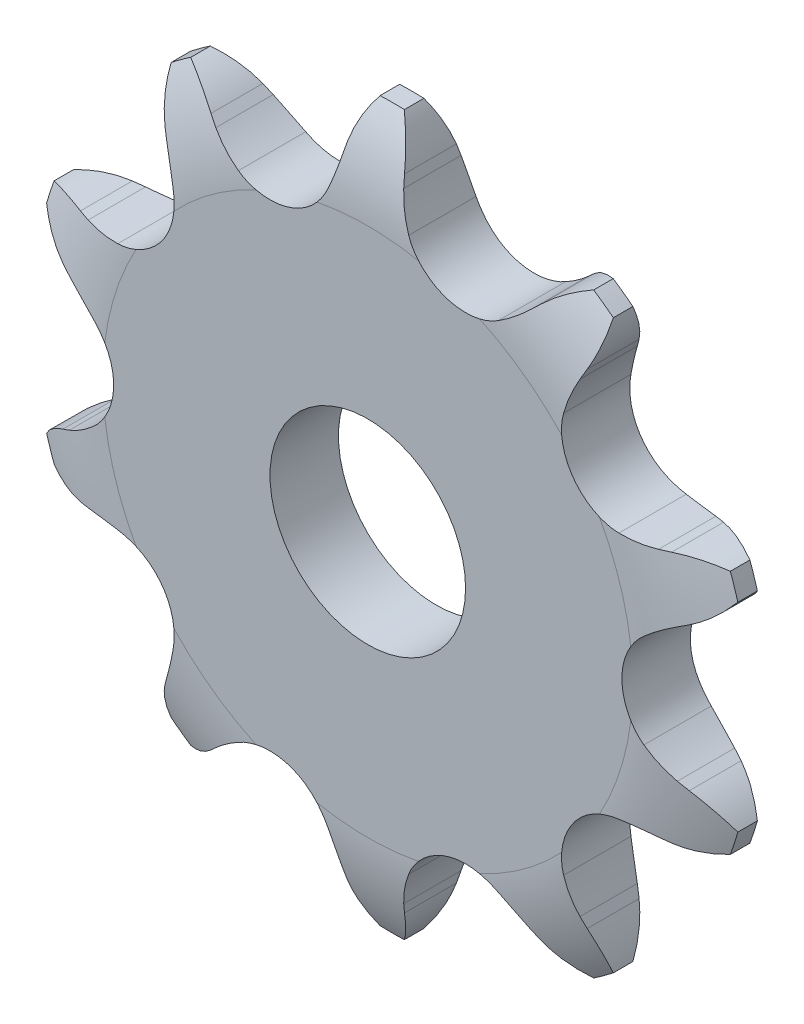
SolidWorks part; units mm, degrees
ref_plane "Front Plane" through (0, 0, 0) normal (0, 0, 1) x (1, 0, 0)
ref_plane "Top Plane" through (0, 0, 0) normal (0, 1, 0) x (1, 0, 0)
ref_plane "Right Plane" through (0, 0, 0) normal (1, 0, 0) x (0, 0, -1)
sketch "Sketch0" plane through (0, 0, 0) normal (0, 0, 1) x (1, 0, 0)
  line L0 (4, -12.3107) -> (0, 0) construction
  line L1 (0, 0) -> (10.4721, -7.6085) construction
  line L2 (0, 0) -> (-4, -12.3107) construction
  line L3 (4, -12.3107) -> (10.4721, -7.6085) construction
  line L4 (4, -12.3107) -> (-4, -12.3107) construction
  line L5 (6.7522, -11.2745) -> (6.4407, -10.9799)
  line L6 (4, -12.3107) -> (0, -13.6104) construction
  line L7 (1.1643, -13.0901) -> (1.2432, -12.6687)
  line L8 (0, -12.3107) -> (0, -14.7107) construction
  line L9 (5.3137, -10.1244) -> (1.9398, -15.7394) construction
  line L10 (0, 0) -> (0, -12.3107) construction
  line L11 (6.4407, -10.9799) -> (1.9398, -15.7394) construction
  line L12 (0, -14.7107) -> (0, -15.3022) construction
  line L13 (9.6631, -8.1962) -> (6.7522, -11.2745) construction
  circle A0 centre (0, 0) radius 14.7107 construction
  circle A1 centre (0, 0) radius 12.9443 construction
  arc A2 (-4.0031, -16.4269) -> (12.8941, -10.9367) centre (0, 0) ccw
  circle A3 centre (0, 0) radius 15.3022 construction
  circle A4 centre (4, -12.3107) radius 2.5 construction
  arc A7 (5.3137, -10.1244) -> (1.6522, -11.3141) centre (4, -12.3107) ccw
  circle A8 centre (4, -12.3107) radius 2.5506 construction
  arc A9 (6.7522, -11.2745) -> (12.8941, -10.9367) centre (9.6631, -8.1962) ccw
  arc A10 (6.4407, -10.9799) -> (5.3137, -10.1244) centre (1.9398, -15.7394) ccw
  arc A11 (1.1643, -13.0901) -> (-4.0031, -16.4269) centre (-3, -12.3107) cw
  arc A12 (1.2432, -12.6687) -> (1.6522, -11.3141) centre (7.682, -13.8737) cw
  dimension "D1" = 2.5506
  dimension "R" = 2.5506
sketch "Sketch1" plane through (0, 0, 0) normal (1, 0, 0) x (0, 0, -1)
  line L0 (1.4, 0) -> (-1.4, 0)
  line L1 (-1.4, 0) -> (-1.4, 10.8378)
  line L2 (-1.4, 12.9443) -> (0, 12.9443) construction
  line L3 (-0.4, 14.7107) -> (0.4, 14.7107)
  line L5 (1.4, 10.8378) -> (1.4, 0)
  line L7 (0, 14.7107) -> (0, 0) construction
  line L8 (-1.4, 10.8378) -> (1.4, 10.8378) construction
  line L9 (0, 14.7107) -> (0, -14.7107) construction
  line L10 (-1.4, 10.8378) -> (-1.4, 14.7107) construction
  line L11 (-1.4, 14.7107) -> (-0.4, 14.7107) construction
  line L12 (0.4, 14.7107) -> (1.4, 14.7107) construction
  line L13 (1.4, 14.7107) -> (1.4, 10.8378) construction
  line L14 (0, 0) -> (-6.4008, 0) construction
  line L15 (-1.4, 12.9443) -> (-1.4, 7.6443) construction
  line L22 (1.4, 0) -> (-10.6, 0) construction
  line L24 (-1.4, 0) -> (-1.4, 7.6443) construction
  arc A0 (-0.4, 14.7107) -> (-1.4, 10.8378) centre (6.6, 10.8378) ccw
  arc A1 (0.4, 14.7107) -> (1.4, 10.8378) centre (-6.6, 10.8378) cw
  dimension "R" = 8
revolve "Revolve1" add sketch "Sketch1" angle 360 mid plane about L0
extrude "Cut-Extrude1" cut sketch "Sketch0" against normal through all and the other way through all
pattern_circular "CirPattern1" count 10 over 360 about axis through (0, 0, 0) along (0, 0, 1) of "Cut-Extrude1"
sketch "Sketch2" plane through (0, 0, 0) normal (0, 0, 1) x (1, 0, 0)
  circle A0 centre (0, 0) radius 4 construction
  circle A1 centre (0, 0) radius 8.5
  circle A2 centre (0, 0) radius 14.71 construction
  dimension "Bore" = 8
  dimension "Hub Dia." = 17
  dimension "OD" = 29.42
extrude "Boss-Extrude1" add sketch "Sketch2" along normal up to vertex (10.6 mm away) from surface at 1.4 starting at face at (0, 0, 1.4)
sketch "Sketch3" plane through (0, 0, 0) normal (0, 0, 1) x (1, 0, 0)
  circle A0 centre (0, 0) radius 4 construction
  circle A1 centre (0, 0) radius 4
extrude "Cut-Extrude2" cut sketch "Sketch3" along normal through all and the other way through all
sketch "Sketch4" plane through (0, 0, 0) normal (1, 0, 0) x (0, 0, -1)
  line L0 (-10.6, 8.5) -> (-10.6, 8)
  line L1 (-1.4, 14.7107) -> (-3.5, 14.7107)
  line L2 (-1.4, 14.7107) -> (-1.4, 7.6443)
  line L3 (-1.4, 7.6443) -> (-3.5, 7.6443)
  line L4 (-3.5, 14.7107) -> (-3.5, 7.6443)
  line L9 (-10.6, 8) -> (-10.1, 8.5)
  line L10 (-10.1, 8.5) -> (-10.6, 8.5)
  dimension "C" = 0.5
  dimension "D3" = 2.1
revolve "Cut-Revolve1" cut sketch "Sketch4" angle 360 mid plane about L22
sketch "Sketch5" plane through (0, 0, 0) normal (0, 0, 1) x (1, 0, 0)
  circle A0 centre (0, 0) radius 14.71 construction
  circle A1 centre (0, 0) radius 14.71
extrude "Cut-Extrude3" [suppressed] cut sketch "Sketch5" against normal through all and the other way through all flip side to cut
sketch "Sketch6" plane through (0, 0, 1.4) normal (0, 0, 1) x (1, 0, 0)
  circle A0 centre (0, 0) radius 9
  dimension "D1" = 18
extrude "Cut-Extrude4" cut sketch "Sketch6" along normal blind 10
equation "\"360/N@Sketch0\" = 360/\"Teeth@CirPattern1\""
equation "\"Ds@Sketch0\" = 1.005 * \"Dr@Sketch0\" + ( 0.003 * 25.4 ) "
equation "\"R@Sketch0\" = 1/2 * \"Ds@Sketch0\""
equation "\"A@Sketch0\" = 35 +  ( 60 / \"Teeth@CirPattern1\" ) "
equation "\"B@Sketch0\" = 18 -  ( 56 / \"Teeth@CirPattern1\" )"
equation "\"ac@Sketch0\" = 0.8 * \"Dr@Sketch0\""
equation "\"ab@Sketch0\" = 1.4 * \"Dr@Sketch0\""
equation "\"J@Sketch0\" = 0.3 * \"Pitch@Sketch0\""
equation "\"D3@Sketch4\" = \"t@Sketch1\" * 3 / 4"
